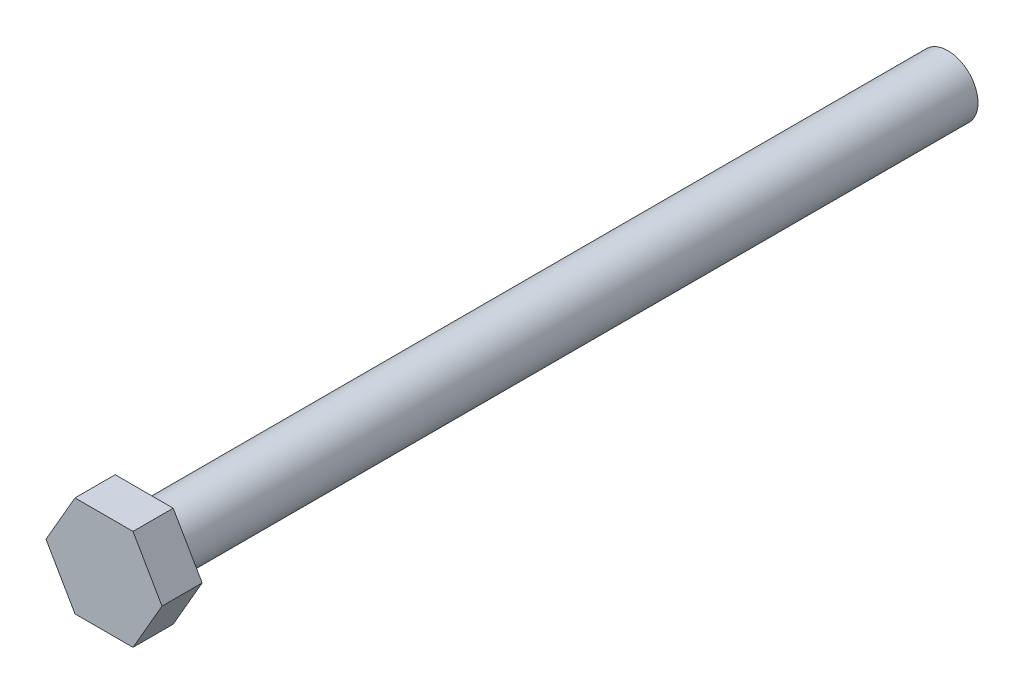
SolidWorks part; units mm, degrees
material "AISI 304"
ref_plane "Front Plane" through (0, 0, 0) normal (0, 0, 1) x (1, 0, 0)
ref_plane "Top Plane" through (0, 0, 0) normal (0, 1, 0) x (1, 0, 0)
ref_plane "Right Plane" through (0, 0, 0) normal (1, 0, 0) x (0, 0, -1)
sketch "Sketch1" plane through (0, 0, 0) normal (0, 0, 1) x (1, 0, 0)
  circle A0 centre (0, 0) radius 3
  dimension "D1" = 6
extrude "Extrude1" add sketch "Sketch1" against normal blind 80
cosmetic thread "Cosmetic Thread1" parameters "D1"=18, "D2"=6.5278
sketch "Sketch2" plane through (0, 0, 0) normal (0, 0, 1) x (1, 0, 0)
  line L1 (-2.8868, 5) -> (-5.7735, 0)
  line L2 (-5.7735, 0) -> (-2.8868, -5)
  line L3 (-2.8868, -5) -> (2.8868, -5)
  line L4 (2.8868, -5) -> (5.7735, 0)
  line L5 (5.7735, 0) -> (2.8868, 5)
  line L6 (2.8868, 5) -> (-2.8868, 5)
  circle A0 centre (0, 0) radius 5 construction
  dimension "D1" = 10
extrude "Extrude2" add sketch "Sketch2" along normal blind 4
